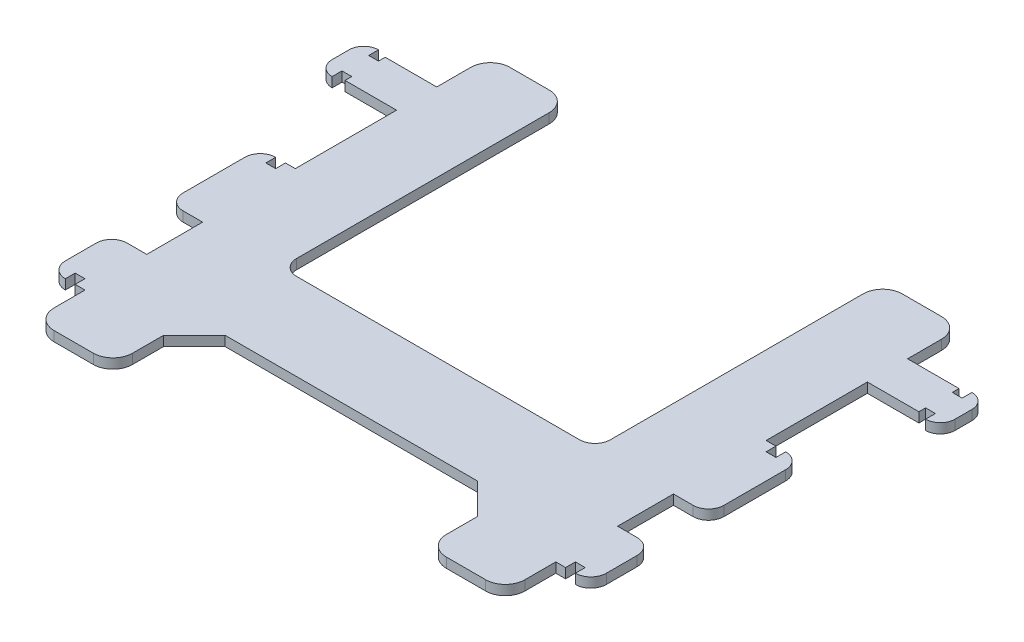
SolidWorks part; units mm, degrees
ref_plane "Front Plane" through (0, 0, 0) normal (0, 0, 1) x (1, 0, 0)
ref_plane "Top Plane" through (0, 0, 0) normal (0, 1, 0) x (1, 0, 0)
ref_plane "Right Plane" through (0, 0, 0) normal (1, 0, 0) x (0, 0, -1)
sketch "Sketch1" plane through (0, 0, 0) normal (0, 1, 0) x (1, 0, 0)
  line L1 (-98.425, 60) -> (98.425, 60)
  line L2 (-98.425, 60) -> (-98.425, -60)
  line L3 (-98.425, -60) -> (98.425, -60)
  line L4 (98.425, 60) -> (98.425, -60)
  line L5 (-98.425, 60) -> (98.425, -60) construction
  line L6 (-98.425, -60) -> (98.425, 60) construction
  point P0 (0, 0)
  dimension "D1" = 196.85
  dimension "D2" = 120
extrude "Boss-Extrude1" add sketch "Sketch1" along normal blind 3.175
sketch "Sketch2" plane through (0, 0, 0) normal (0, 1, 0) x (1, 0, 0)
  line L1 (98.425, -60) -> (98.425, 60) construction
  line L2 (76.2, -18.9667) -> (82.55, -18.9667)
  line L3 (98.425, 0) -> (98.425, -60)
  line L4 (98.425, -60) -> (-98.425, -60)
  line L5 (-98.425, -60) -> (-98.425, 60)
  line L6 (-98.425, 60) -> (98.425, 60)
  line L7 (98.425, 60) -> (98.425, 0)
  line L8 (76.2, -59.2339) -> (76.2, 60)
  line L9 (-76.2, -59.2339) -> (-76.2, 60)
  line L10 (76.2, 57.8113) -> (76.2, -57.0452)
  line L11 (76.2, 57.8113) -> (92.8687, 57.8113)
  line L12 (76.2, -57.0452) -> (79.375, -57.0452)
  line L13 (-76.2, -57.0452) -> (-98.425, -57.0452)
  line L14 (-76.2, 57.8113) -> (-96.0438, 57.8113)
  line L15 (-76.2, 57.8113) -> (76.2, 57.8113)
  line L16 (-76.2, -57.0452) -> (76.2, -57.0452)
  line L17 (76.2, 57.8113) -> (76.2, 42.8081)
  line L18 (76.2, 42.8081) -> (92.8688, 42.8081)
  line L19 (76.2, 42.8081) -> (87.3125, 42.8081)
  line L20 (87.3125, 42.8081) -> (92.8688, 42.8081)
  line L21 (92.8688, 42.8081) -> (92.8687, 57.8113)
  line L22 (92.8688, 42.8081) -> (92.8688, 45.9831)
  line L23 (92.8687, 57.8113) -> (92.8687, 54.6363)
  line L24 (92.8687, 54.6363) -> (96.0437, 54.6363)
  line L25 (92.8688, 45.9831) -> (96.0438, 45.9831)
  line L26 (96.0438, 45.9831) -> (96.0438, 42.8081)
  line L27 (96.0437, 54.6363) -> (96.0437, 57.8113)
  line L28 (96.0438, 42.8081) -> (96.0438, 45.9831)
  line L30 (96.0437, 57.8113) -> (96.0437, 54.6363)
  line L33 (100.8062, 53.0488) -> (100.8062, 47.5706)
  line L34 (-100.8062, 53.0488) -> (-100.8062, 47.5706)
  line L35 (-96.0437, 54.6363) -> (-96.0438, 57.8113)
  line L36 (-76.2, 57.8113) -> (-96.0438, 57.8113)
  line L37 (-92.8687, 54.6363) -> (-96.0437, 54.6363)
  line L38 (-96.0438, 45.9831) -> (-96.0438, 42.8081)
  line L39 (-92.8688, 45.9831) -> (-96.0438, 45.9831)
  line L40 (-92.8688, 42.8081) -> (-92.8688, 57.8113)
  line L41 (-76.2, 42.8081) -> (-96.0438, 42.8081)
  line L42 (76.2, 42.8081) -> (76.2, 11.0333)
  line L43 (76.2, 11.0333) -> (76.2, -18.9667)
  line L44 (76.2, 11.0333) -> (79.375, 11.0333)
  line L45 (76.2, -18.9667) -> (76.2, -37.0452)
  line L46 (76.2, -37.0452) -> (76.2, -57.0452)
  line L47 (76.2, -59.2339) -> (76.2, -60)
  line L48 (-76.2, -59.2339) -> (-76.2, -60)
  line L49 (76.2, -37.0452) -> (82.55, -37.0452)
  line L50 (76.2, -57.0452) -> (79.375, -57.0452)
  line L51 (-76.2, -57.0452) -> (-98.425, -57.0452)
  line L52 (-76.2, -37.0452) -> (-98.425, -37.0452)
  line L53 (-76.2, -18.9667) -> (-98.425, -18.9667)
  line L54 (-76.2, 11.0333) -> (-98.425, 11.0333)
  line L55 (76.2, -57.0452) -> (79.375, -57.0452)
  line L56 (79.375, -57.0452) -> (79.375, -53.8702)
  line L57 (79.375, -57.0452) -> (79.375, -53.8702)
  line L58 (79.375, -53.8702) -> (82.55, -53.8702)
  line L59 (82.55, -53.8702) -> (82.55, -57.0452)
  line L60 (76.2, 11.0333) -> (79.375, 11.0333)
  line L61 (79.375, 11.0333) -> (79.375, 7.8583)
  line L62 (79.375, 7.8583) -> (82.55, 7.8583)
  line L63 (82.55, 7.8583) -> (82.55, 11.0333)
  line L64 (87.55, -52.0452) -> (87.55, -42.0452)
  line L65 (76.2, 11.0333) -> (76.2, -18.9667)
  line L66 (-79.375, -57.0452) -> (-79.375, -53.8702)
  line L67 (-79.375, -53.8702) -> (-82.55, -53.8702)
  line L68 (-82.55, -53.8702) -> (-82.55, -57.0452)
  line L69 (-87.55, -52.0452) -> (-87.55, -42.0452)
  line L70 (79.375, -18.9667) -> (76.2, -18.9667)
  line L71 (82.55, 11.0333) -> (82.55, 7.8583)
  line L72 (-87.55, -13.9667) -> (-87.55, 6.0333)
  line L73 (87.55, -13.9667) -> (87.55, 6.0333)
  line L74 (-82.55, 7.8583) -> (-82.55, 11.0333)
  line L75 (-79.375, 7.8583) -> (-82.55, 7.8583)
  line L76 (-79.375, 11.0333) -> (-79.375, 7.8583)
  line L77 (161.0828, 42.8206) -> (161.0828, 37.3423)
  arc A0 (96.0438, 42.8081) -> (100.8062, 47.5706) centre (96.0438, 47.5706) ccw
  arc A1 (96.0437, 57.8113) -> (100.8062, 53.0488) centre (96.0438, 53.0488) cw
  arc A2 (-96.0438, 57.8113) -> (-100.8062, 53.0488) centre (-96.0438, 53.0488) ccw
  arc A3 (-96.0438, 42.8081) -> (-100.8062, 47.5706) centre (-96.0438, 47.5706) cw
  arc A4 (82.55, -37.0452) -> (87.55, -42.0452) centre (82.55, -42.0452) cw
  arc A5 (82.55, -57.0452) -> (87.55, -52.0452) centre (82.55, -52.0452) ccw
  arc A6 (82.55, 11.0333) -> (87.55, 6.0333) centre (82.55, 6.0333) cw
  arc A7 (82.55, -18.9667) -> (87.55, -13.9667) centre (82.55, -13.9667) ccw
  arc A8 (-82.55, -57.0452) -> (-87.55, -52.0452) centre (-82.55, -52.0452) cw
  arc A9 (-82.55, -37.0452) -> (-87.55, -42.0452) centre (-82.55, -42.0452) ccw
  arc A10 (-82.55, -18.9667) -> (-87.55, -13.9667) centre (-82.55, -13.9667) cw
  arc A11 (-82.55, 11.0333) -> (-87.55, 6.0333) centre (-82.55, 6.0333) ccw
  arc A12 (156.3203, 32.5798) -> (161.0828, 37.3423) centre (156.3203, 37.3423) ccw
  arc A13 (156.3203, 47.5831) -> (161.0828, 42.8206) centre (156.3203, 42.8206) cw
  point P17 (76.2, 0.3831)
  point P22 (76.2, 0.3831)
extrude "Cut-Extrude3" cut sketch "Sketch2" along normal blind 3.175 contours A9 L52 L5 L13 A8 L69 | L9 L53 L5 L52 | A11 L54 L5 L53 A10 L72 | L41 A3 L5 L54 L9 | A2 L36 L14 L9 L6 L5 | L9 L15 L8 L6 | L27 A1 L7 L6 L8 L11 L21 L24 | A7 L2 L10 L49 A4 L64 A5 L59 L58 L56 L12 L8 L47 L4 L3 L7 A0 L26 L25 L21 L18 L44 L61 L62 L63 A6 L73 | L9 L48 L4 L47 L8 L16 | L48 L9 L13 L51 L5 L4 | L67 L68 L51 L66 | L76 L54 L74 L75 | L41 L40 L39 L38 | L37 L40 L36 L35
sketch "Sketch5" plane through (0, 0, 0) normal (0, 1, 0) x (1, 0, 0)
  line L0 (96.0437, 57.8113) -> (96.0438, 53.0488)
  line L1 (96.0437, 54.6363) -> (96.0438, 45.9831)
  line L2 (96.0437, 50.3097) -> (97.5536, 50.3097)
  line L3 (100.8063, 53.0488) -> (100.8063, 47.5706)
  line L4 (0, 0) -> (0, 30.6706)
  line L5 (-100.8063, 53.0488) -> (-100.8063, 47.5706)
  line L6 (96.0438, 45.9831) -> (96.0437, 42.8081)
  line L7 (98.425, 57.1732) -> (98.425, 43.4461)
  line L8 (-98.425, 57.1732) -> (-98.425, 43.4461)
  arc A0 (96.0437, 57.8113) -> (100.8063, 53.0488) centre (96.0438, 53.0488) cw
  arc A1 (96.0437, 42.8081) -> (100.8063, 47.5706) centre (96.0438, 47.5706) ccw
  arc A2 (-96.0437, 42.8081) -> (-100.8063, 47.5706) centre (-96.0438, 47.5706) cw
  arc A3 (-96.0437, 57.8113) -> (-100.8063, 53.0488) centre (-96.0438, 53.0488) ccw
extrude "Boss-Extrude3" add sketch "Sketch5" along normal blind 3.175 contours L8 A3 L5 A2 | L7 A1 L3 A0
sketch "Sketch6" plane through (0, 0, 0) normal (0, 1, 0) x (1, 0, 0)
  line L0 (50.8, -57.0452) -> (76.2, -57.0452)
  line L2 (92.8687, 57.8113) -> (-92.8688, 57.8113) construction
  line L3 (76.2, 26.9207) -> (76.2, 57.8113)
  line L4 (-76.2, 57.8113) -> (-76.2, 67.8113)
  line L5 (-76.2, 67.8113) -> (-76.2, 57.8113)
  line L6 (-50.8, 67.8113) -> (-50.8, 57.8113)
  line L7 (50.8, 57.8113) -> (-50.8, 57.8113)
  line L8 (50.8, 67.8113) -> (50.8, 57.8113)
  line L9 (76.2, 11.0333) -> (76.2, 42.8081) construction
  line L10 (-50.8, -57.0452) -> (50.8, -57.0452)
  line L11 (-40.8, -47.0452) -> (40.8, -47.0452)
  line L12 (57.15, 74.1613) -> (69.85, 74.1613)
  line L13 (76.2, 57.8113) -> (76.2, 67.8113)
  line L14 (-50.8, -57.0452) -> (-50.8, -57.8113)
  line L16 (76.2, -57.8113) -> (76.2, -67.8113)
  line L17 (57.15, -74.1613) -> (69.85, -74.1613)
  line L18 (-57.15, 74.1613) -> (-69.85, 74.1613)
  line L19 (50.8, -67.8113) -> (50.8, -57.8113)
  line L20 (-50.8, -67.8113) -> (-50.8, -57.8113)
  line L21 (-76.2, -57.8113) -> (-76.2, -67.8113)
  line L22 (-57.15, -74.1613) -> (-69.85, -74.1613)
  line L23 (-50.8, 57.8113) -> (-50.8, -13.9667)
  line L33 (50.8, 57.8113) -> (50.8, -13.9667)
  line L34 (-76.2, -57.8113) -> (-76.2, -57.0452)
  line L35 (79.375, -57.0452) -> (-79.375, -57.0452) construction
  line L36 (-76.2, -57.0452) -> (-50.8, -57.0452)
  line L37 (76.2, -57.8113) -> (76.2, -57.0452)
  line L38 (-45.8, -18.9667) -> (45.8, -18.9667)
  line L40 (45.8, -18.9667) -> (-45.8, -18.9667)
  line L46 (50.8, -57.0452) -> (40.8, -47.0452)
  line L47 (50.8, 57.8113) -> (50.8, -13.9667)
  line L48 (50.8, -57.0452) -> (50.8, -57.8113)
  line L49 (-40.8, -47.0452) -> (40.8, -47.0452)
  line L50 (-50.8, -57.0452) -> (-40.8, -47.0452)
  line L51 (50.8, -57.0452) -> (50.8, -57.8113)
  arc A0 (50.8, 67.8113) -> (57.15, 74.1613) centre (57.15, 67.8113) cw
  arc A1 (76.2, 67.8113) -> (69.85, 74.1613) centre (69.85, 67.8113) ccw
  arc A2 (76.2, -67.8113) -> (69.85, -74.1613) centre (69.85, -67.8113) cw
  arc A3 (50.8, -67.8113) -> (57.15, -74.1613) centre (57.15, -67.8113) ccw
  arc A4 (-76.2, 67.8113) -> (-69.85, 74.1613) centre (-69.85, 67.8113) cw
  arc A5 (-50.8, 67.8113) -> (-57.15, 74.1613) centre (-57.15, 67.8113) ccw
  arc A6 (-50.8, -67.8113) -> (-57.15, -74.1613) centre (-57.15, -67.8113) cw
  arc A7 (-76.2, -67.8113) -> (-69.85, -74.1613) centre (-69.85, -67.8113) ccw
  arc A8 (-45.8, -18.9667) -> (-50.8, -13.9667) centre (-45.8, -13.9667) cw
  arc A9 (45.8, -18.9667) -> (50.8, -13.9667) centre (45.8, -13.9667) ccw
  dimension "D4" = 5
extrude "Cut-Extrude5" cut sketch "Sketch6" along normal blind 6.175 contours L38 A9 L33 L7 L23 A8 | L50 L10 L46 L11
sketch "Sketch7" plane through (0, 0, 0) normal (0, 1, 0) x (1, 0, 0)
  line L0 (-50.8, -57.0452) -> (-50.8, -67.0452)
  line L1 (50.8, 57.8113) -> (76.2, 57.8113)
  line L3 (76.2, -57.0452) -> (76.2, -67.0452)
  line L4 (92.8687, 57.8113) -> (50.8, 57.8113) construction
  line L5 (76.2, 57.8113) -> (92.8687, 57.8113)
  line L6 (76.2, 57.8113) -> (76.2, 67.8113)
  line L7 (50.8, 57.8113) -> (50.8, 67.8113)
  line L8 (69.85, 74.1613) -> (57.15, 74.1613)
  line L11 (-76.2, 57.8113) -> (-76.2, 67.8113)
  line L12 (-69.85, 74.1613) -> (-57.15, 74.1613)
  line L13 (-50.8, 57.8113) -> (-50.8, 67.8113)
  line L14 (-76.2, 57.8113) -> (-50.8, 57.8113)
  line L15 (-50.8, -57.0452) -> (-79.375, -57.0452) construction
  line L16 (-76.2, -57.0452) -> (-76.2, -67.0452)
  line L17 (-69.85, -73.3952) -> (-57.15, -73.3952)
  line L18 (69.85, -73.3952) -> (57.15, -73.3952)
  line L19 (50.8, -57.0452) -> (50.8, -67.0452)
  line L20 (-76.2, -57.0452) -> (-50.8, -57.0452)
  line L21 (50.8, -57.0452) -> (76.2, -57.0452)
  arc A0 (50.8, 67.8113) -> (57.15, 74.1613) centre (57.15, 67.8113) cw
  arc A1 (76.2, 67.8113) -> (69.85, 74.1613) centre (69.85, 67.8113) ccw
  arc A2 (-76.2, 67.8113) -> (-69.85, 74.1613) centre (-69.85, 67.8113) cw
  arc A3 (-50.8, 67.8113) -> (-57.15, 74.1613) centre (-57.15, 67.8113) ccw
  arc A4 (-76.2, -67.0452) -> (-69.85, -73.3952) centre (-69.85, -67.0452) ccw
  arc A5 (-50.8, -67.0452) -> (-57.15, -73.3952) centre (-57.15, -67.0452) cw
  arc A6 (76.2, -67.0452) -> (69.85, -73.3952) centre (69.85, -67.0452) cw
  arc A7 (50.8, -67.0452) -> (57.15, -73.3952) centre (57.15, -67.0452) ccw
  dimension "D1" = 10
extrude "Boss-Extrude4" add sketch "Sketch7" along normal blind 3.175 contours L13 A3 L12 A2 L11 L14 | L6 A1 L8 A0 L7 L1 | A5 L0 L20 L16 A4 L17 | L19 A7 L18 A6 L3 L21
sketch "Sketch8" plane through (0, 0, 0) normal (0, 1, 0) x (1, 0, 0)
  line L0 (76.2, 57.8113) -> (76.2, 42.8081)
  line L1 (76.2, 11.0333) -> (76.2, 42.8081) construction
  line L2 (76.2, 42.8081) -> (92.8688, 42.8081)
  line L3 (92.8688, 42.8081) -> (92.8687, 57.8113)
  line L4 (92.8687, 57.8113) -> (76.2, 57.8113)
  line L5 (92.8688, 42.8081) -> (92.8688, 43.8081)
  line L6 (92.8688, 43.8081) -> (76.2, 43.8081)
  line L7 (92.8687, 57.8113) -> (92.8688, 56.8113)
  line L8 (92.8688, 56.8113) -> (76.2, 56.8113)
  dimension "D1" = 1
  dimension "D2" = 1
extrude "Cut-Extrude6" cut sketch "Sketch8" along normal blind 4 contours L3 L6 L0 L2 | L8 L3 L4 L0
sketch "Sketch9" plane through (0, 0, 0) normal (0, 1, 0) x (1, 0, 0)
  line L0 (-76.2, 42.8081) -> (-76.2, 57.8113)
  line L1 (-76.2, 57.8113) -> (-92.8688, 57.8113)
  line L2 (-92.8688, 57.8113) -> (-92.8688, 42.8081)
  line L3 (-92.8688, 42.8081) -> (-76.2, 42.8081)
  line L4 (-92.8688, 42.8081) -> (-92.8688, 43.8081)
  line L5 (-92.8688, 43.8081) -> (-76.2, 43.8081)
  line L6 (-92.8688, 57.8113) -> (-92.8688, 56.8113)
  line L7 (-92.8688, 56.8113) -> (-76.2, 56.8113)
  dimension "D1" = 1
  dimension "D2" = 1
extrude "Cut-Extrude7" cut sketch "Sketch9" along normal blind 4 contours L2 L7 L0 L1 | L5 L2 L3 L0
